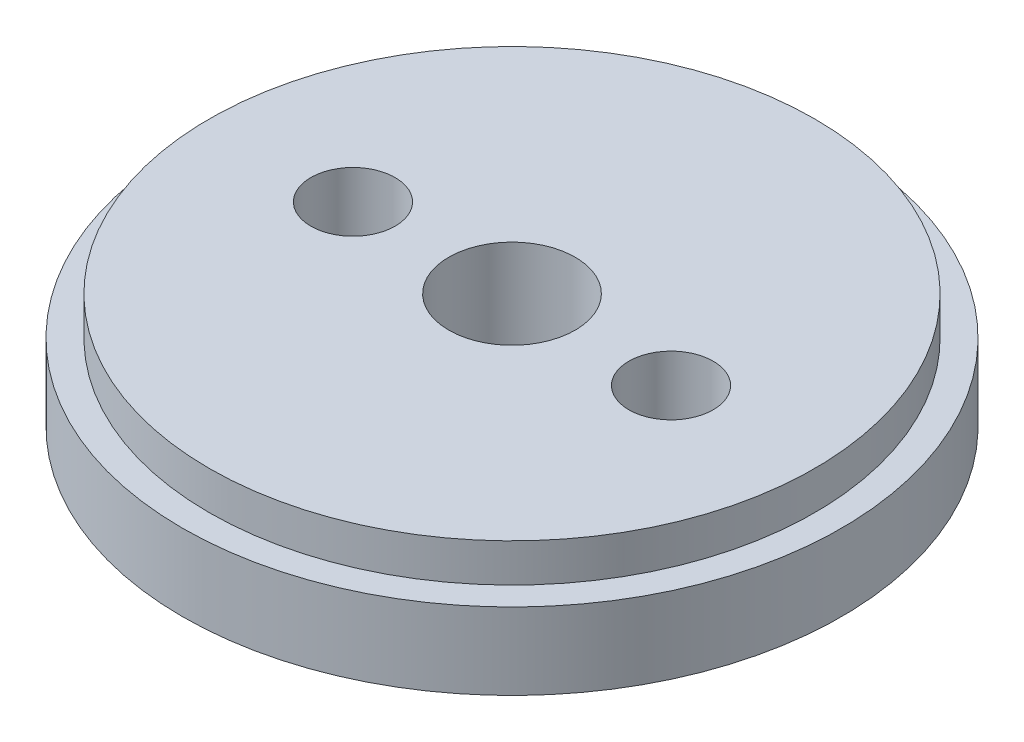
SolidWorks part; units mm, degrees
ref_plane "Front Plane" through (0, 0, 0) normal (0, 0, 1) x (1, 0, 0)
ref_plane "Top Plane" through (0, 0, 0) normal (0, 1, 0) x (1, 0, 0)
ref_plane "Right Plane" through (0, 0, 0) normal (1, 0, 0) x (0, 0, -1)
sketch "Sketch1" plane through (0, 0, 0) normal (0, 1, 0) x (1, 0, 0)
  circle A0 centre (0, 0) radius 17.2
  dimension "D1" = 34.4
extrude "Boss-Extrude1" add sketch "Sketch1" along normal blind 6
sketch "Sketch2" plane through (0, 6, 0) normal (0, 1, 0) x (1, 0, 0)
  circle A0 centre (0, 0) radius 15.8
  dimension "D1" = 31.6
extrude "Cut-Extrude1" cut sketch "Sketch2" against normal blind 2 flip side to cut
sketch "Sketch3" plane through (0, 6, 0) normal (0, 1, 0) x (1, 0, 0)
  line L0 (-22.4911, 0) -> (26.1714, 0) construction
  line L1 (0, 22.3766) -> (0, -23.9749) construction
  line L2 (-17.2, 0) -> (-8.3, 0)
  circle A0 centre (0, 0) radius 3.3
  circle A1 centre (0, 0) radius 17.2 construction
  circle A2 centre (-8.3, 0) radius 2.2
  circle A3 centre (8.3, 0) radius 2.2
  circle A4 centre (0, 0) radius 15.8 construction
  circle A5 centre (0, 0) radius 15.8
  point P14 (-15.8, 0)
  dimension "D1" = 8.3
  dimension "D3" = 4.4
  dimension "D4" = 6.6
  dimension "D5" = 31.6
  dimension "D2" = 7.5
extrude "Cut-Extrude2" cut sketch "Sketch3" against normal through all
sketch "Sketch5" plane through (0, 6, 0) normal (0, 1, 0) x (1, 0, 0)
  line L0 (-8.3, -2.2) -> (21.4696, -2.2) construction
  line L1 (-8.3, -1.8) -> (21.4696, -1.8) construction
  line L2 (-8.3, -3) -> (21.4696, -3) construction
  line L3 (15.6971, -1.8) -> (-15.6971, -1.8)
  line L4 (21.4696, -3) -> (-15.5126, -3)
  circle A0 centre (-8.3, 0) radius 2.2 construction
  circle A1 centre (0, 0) radius 15.8 construction
  circle A2 centre (0, 0) radius 15.8 construction
  dimension "D1" = 0.4
  dimension "D2" = 1.2
